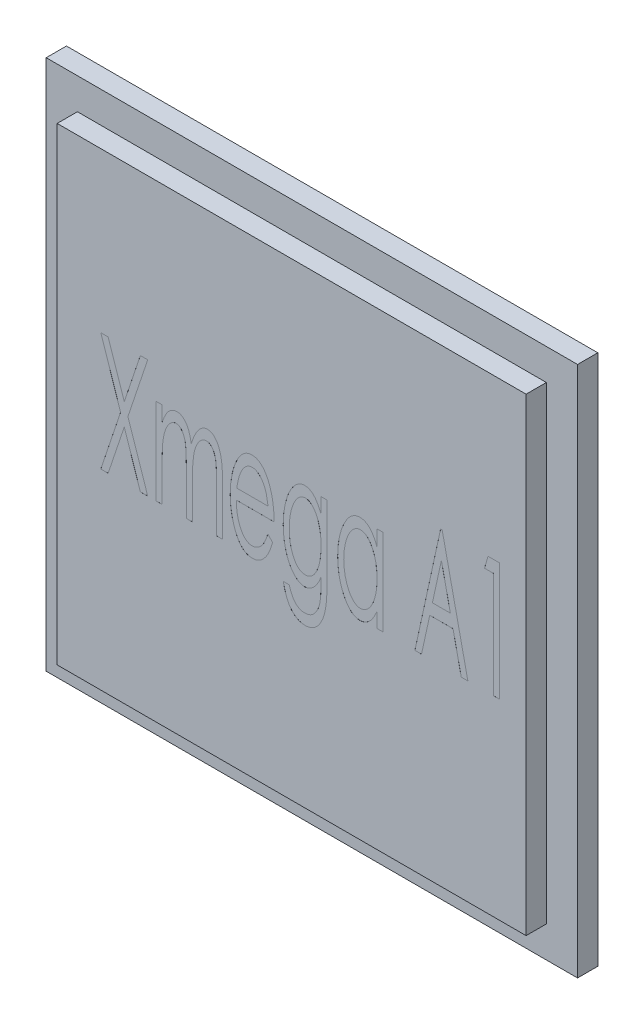
SolidWorks part; units mm, degrees
ref_plane "Přední rovina" through (0, 0, 0) normal (0, 0, 1) x (1, 0, 0)
ref_plane "Horní rovina" through (0, 0, 0) normal (0, 1, 0) x (1, 0, 0)
ref_plane "Pravá rovina" through (0, 0, 0) normal (1, 0, 0) x (0, 0, -1)
sketch "Skica1" plane through (0, 0, 0) normal (0, 0, 1) x (1, 0, 0)
  line L1 (6.95, -6.95) -> (-6.95, -6.95)
  line L2 (6.95, -6.95) -> (6.95, 6.95)
  line L3 (6.95, 6.95) -> (-6.95, 6.95)
  line L4 (-6.95, -6.95) -> (-6.95, 6.95)
  line L5 (6.95, -6.95) -> (-6.95, 6.95) construction
  line L6 (6.95, 6.95) -> (-6.95, -6.95) construction
  point P0 (0, 0)
  dimension "D1" = 13.9
extrude "Přidat vysunutím1" add sketch "Skica1" along normal blind 1.2
sketch "Skica2" plane through (0, 0, 1.2) normal (0, 0, 1) x (1, 0, 0)
  text T0 "Xmega A1" font "Century Gothic" height 3.5
extrude "Odebrat vysunutím1" cut sketch "Skica2" against normal blind 0.001
sketch "Skica4" plane through (0, 0, 0) normal (0, 0, 1) x (1, 0, 0)
  line L1 (-7.875, 7.875) -> (7.875, 7.875)
  line L2 (-7.875, 7.875) -> (-7.875, -7.875)
  line L3 (-7.875, -7.875) -> (7.875, -7.875)
  line L4 (7.875, 7.875) -> (7.875, -7.875)
  line L5 (-7.875, 7.875) -> (7.875, -7.875) construction
  line L6 (-7.875, -7.875) -> (7.875, 7.875) construction
  line L7 (6.95, 6.95) -> (-6.95, 6.95)
  line L8 (6.95, 6.95) -> (6.95, -6.95)
  line L9 (6.95, -6.95) -> (-6.95, -6.95)
  line L10 (-6.95, 6.95) -> (-6.95, -6.95)
  line L11 (6.95, 6.95) -> (-6.95, -6.95) construction
  line L12 (6.95, -6.95) -> (-6.95, 6.95) construction
  point P0 (0, 0)
  point P6 (0, 0)
  dimension "D1" = 15.75
extrude "Přidat vysunutím3" add sketch "Skica4" along normal blind 0.6
